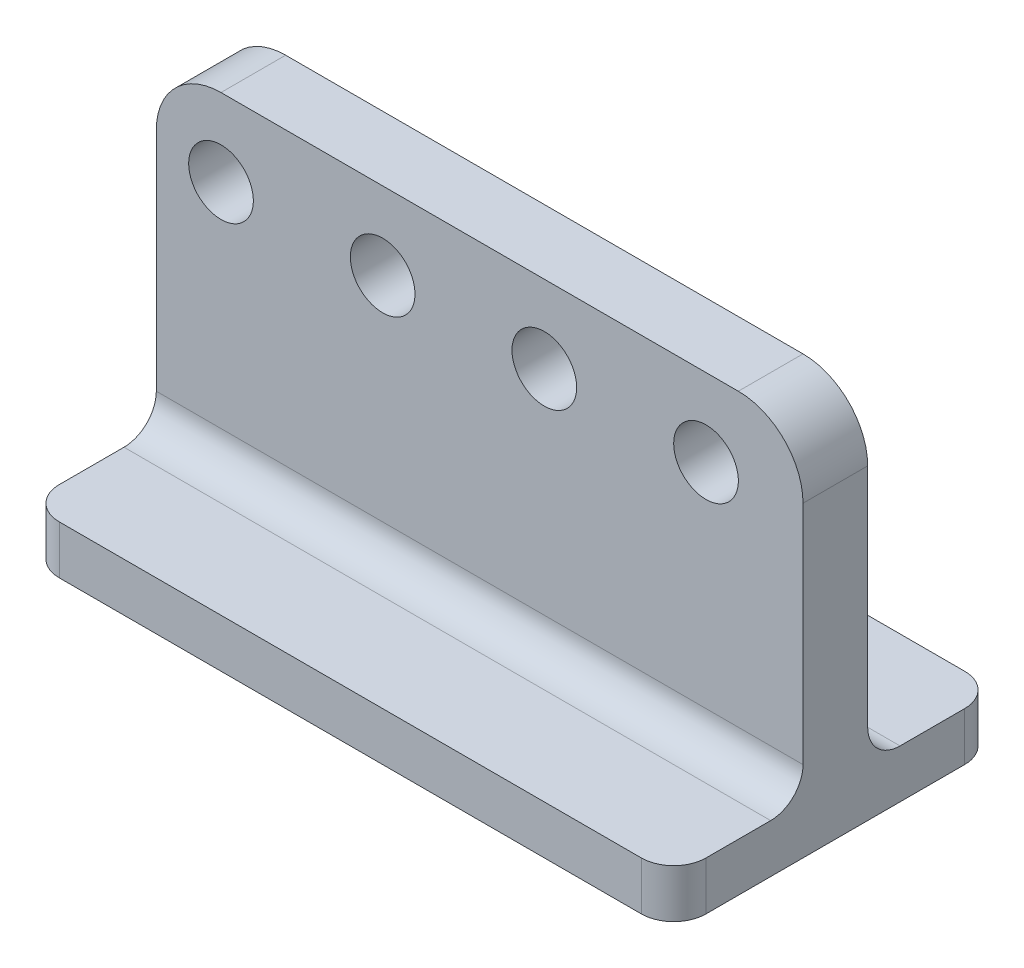
SolidWorks part; units mm, degrees
ref_plane "Front Plane" through (0, 0, 0) normal (0, 0, 1) x (1, 0, 0)
ref_plane "Top Plane" through (0, 0, 0) normal (0, 1, 0) x (1, 0, 0)
ref_plane "Right Plane" through (0, 0, 0) normal (1, 0, 0) x (0, 0, -1)
sketch "Sketch1" plane through (0, 0, 0) normal (0, 1, 0) x (1, 0, 0)
  line L1 (4.4287, 15.5005) -> (55.2287, 15.5005)
  line L2 (4.4287, 15.5005) -> (4.4287, -9.8995)
  line L3 (4.4287, -9.8995) -> (55.2287, -9.8995)
  line L4 (55.2287, 15.5005) -> (55.2287, -9.8995)
  dimension "D1" = 50.8
  dimension "D2" = 25.4
extrude "Boss-Extrude1" add sketch "Sketch1" along normal blind 3.81
sketch "Sketch2" plane through (0, 3.81, 0) normal (0, 1, 0) x (1, 0, 0)
  line L0 (4.4287, 15.5005) -> (4.4287, -9.8995) construction
  line L1 (4.4287, 5.3405) -> (55.2287, 5.3405)
  line L2 (4.4287, 5.3405) -> (4.4287, 0.2605)
  line L3 (4.4287, 0.2605) -> (55.2287, 0.2605)
  line L4 (55.2287, 5.3405) -> (55.2287, 0.2605)
  line L5 (55.2287, -9.8995) -> (55.2287, 15.5005) construction
  line L6 (55.2287, 15.5005) -> (4.4287, 15.5005) construction
  dimension "D1" = 5.08
  dimension "D2" = 10.16
extrude "Boss-Extrude2" add sketch "Sketch2" along normal blind 25.4
sketch "Sketch3" plane through (0, 0, -5.3405) normal (0, 0, -1) x (-1, 0, 0)
  line L0 (-29.8287, 3.81) -> (-29.8287, 23.114)
  line L1 (-55.2287, 3.81) -> (-4.4287, 3.81) construction
  line L2 (-29.8287, 23.114) -> (-55.2287, 23.114)
  line L3 (-55.2287, 29.21) -> (-55.2287, 3.81) construction
  line L4 (-55.2287, 23.114) -> (-4.4287, 23.114)
  line L5 (-4.4287, 29.21) -> (-4.4287, 3.81) construction
  circle A0 centre (-9.5087, 23.114) radius 2.54
  circle A1 centre (-22.2087, 23.114) radius 2.54
  circle A2 centre (-34.9087, 23.114) radius 2.54
  circle A3 centre (-47.6087, 23.114) radius 2.54
  point P12 (0, 0)
  dimension "D2" = 5.08
  dimension "D3" = 5.08
  dimension "D1" = 19.304
  dimension "D4" = 4
extrude "Cut-Extrude1" cut sketch "Sketch3" against normal blind 25.4 contours L4 A0 | L4 A0 | L4 A1 | L4 A1 | L4 A2 | L4 A2 | L4 A3 | L4 A3
fillet "Fillet1" radius 5.08 2 edges at (4.4287, 29.21, -2.8005) (55.2287, 29.21, -2.8005)
fillet "Fillet2" radius 2.54 2 edges at (29.8287, 3.81, -0.2605) (29.8287, 3.81, -5.3405)
fillet "Fillet3" radius 2.54 4 edges at (55.2287, 1.905, 9.8995) (4.4287, 1.905, 9.8995) (55.2287, 1.905, -15.5005) (4.4287, 1.905, -15.5005)
